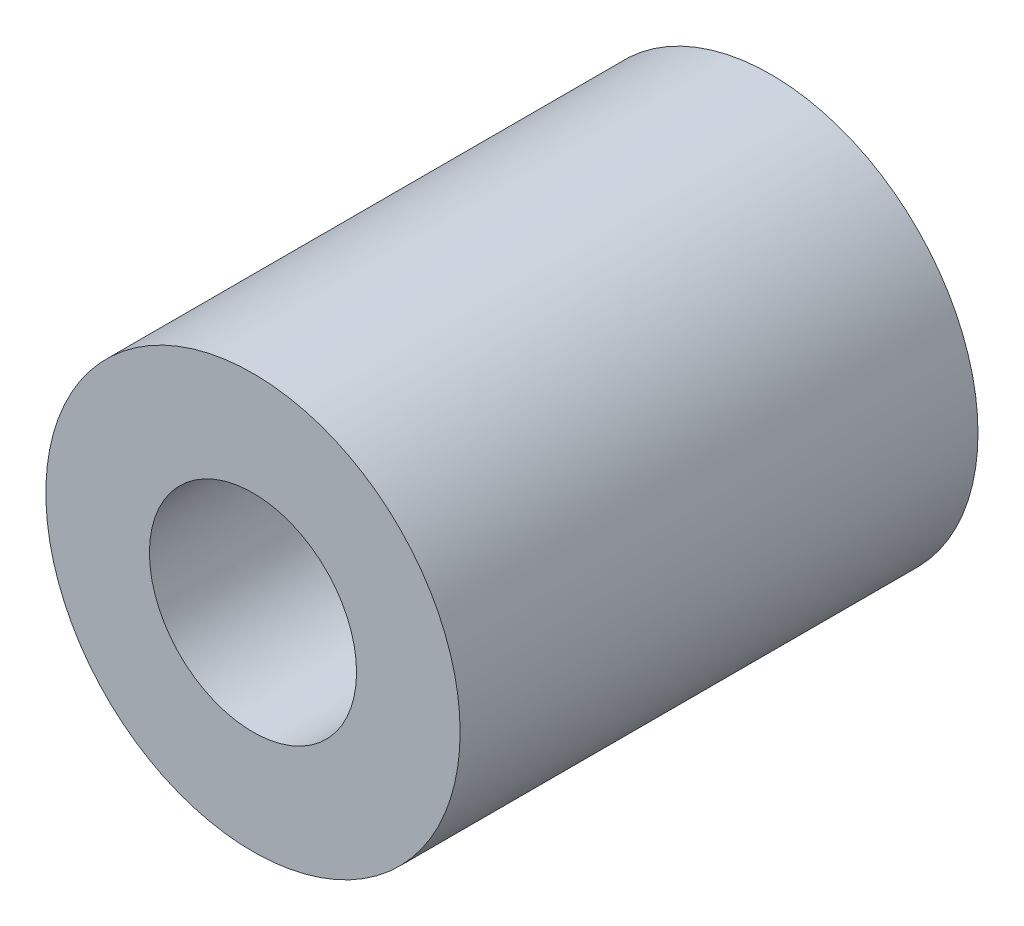
SolidWorks part; units mm, degrees
ref_plane "Front Plane" through (0, 0, 0) normal (0, 0, 1) x (1, 0, 0)
ref_plane "Top Plane" through (0, 0, 0) normal (0, 1, 0) x (1, 0, 0)
ref_plane "Right Plane" through (0, 0, 0) normal (1, 0, 0) x (0, 0, -1)
sketch "Sketch1" plane through (0, 0, 0) normal (0, 0, 1) x (1, 0, 0)
  circle A0 centre (0, 0) radius 2
  circle A1 centre (0, 0) radius 1
  dimension "D1" = 4
  dimension "D2" = 1
extrude "Boss-Extrude1" add sketch "Sketch1" along normal blind 5
